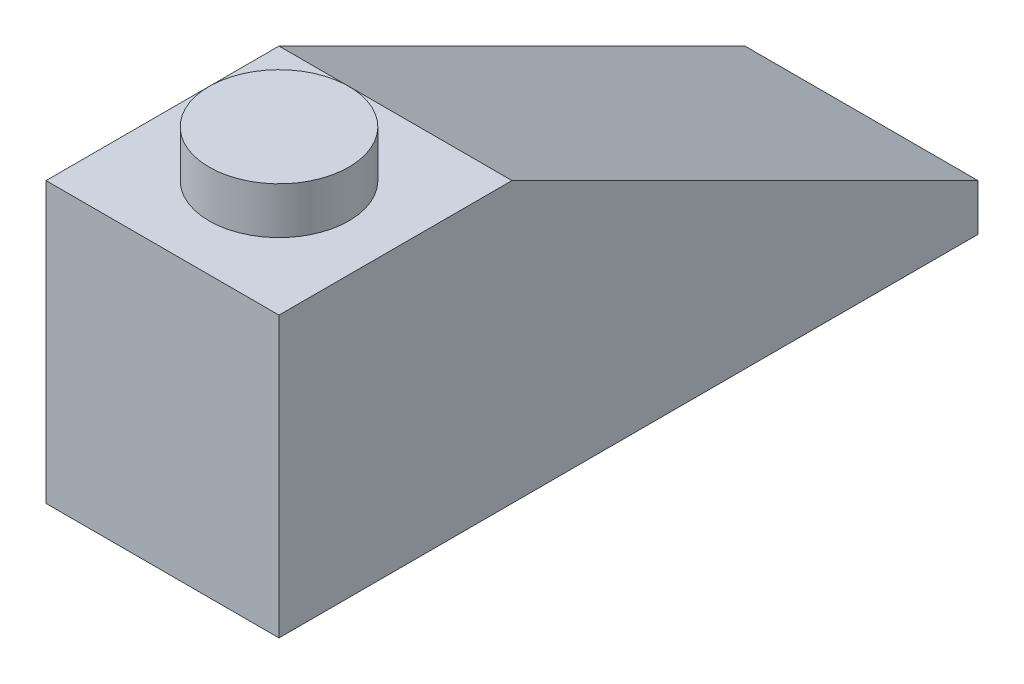
SolidWorks part; units mm, degrees
ref_plane "Front Plane" through (0, 0, 0) normal (0, 0, 1) x (1, 0, 0)
ref_plane "Top Plane" through (0, 0, 0) normal (0, 1, 0) x (1, 0, 0)
ref_plane "Right Plane" through (0, 0, 0) normal (1, 0, 0) x (0, 0, -1)
sketch "Sketch1" plane through (0, 0, 0) normal (1, 0, 0) x (0, 0, -1)
  line L0 (0, 0) -> (24, 0)
  line L2 (8, 9.6) -> (0, 9.6)
  line L3 (0, 9.6) -> (0, 0)
  line L4 (24, 0) -> (24, 1.6)
  line L5 (24, 1.6) -> (8, 9.6)
  dimension "D1" = 9.6
  dimension "D2" = 8
  dimension "D3" = 24
  dimension "D4" = 1.6
extrude "Boss-Extrude1" add sketch "Sketch1" along normal blind 8
sketch "Sketch2" plane through (0, 9.6, 0) normal (0, 1, 0) x (1, 0, 0)
  line L0 (0, 4) -> (4, 4) construction
  line L1 (0, 8) -> (0, 0) construction
  circle A0 centre (4, 4) radius 2.4
  dimension "D2" = 4.8
  dimension "D1" = 4
extrude "Boss-Extrude2" add sketch "Sketch2" along normal blind 1.6
shell "Shell1" thickness 1.6
